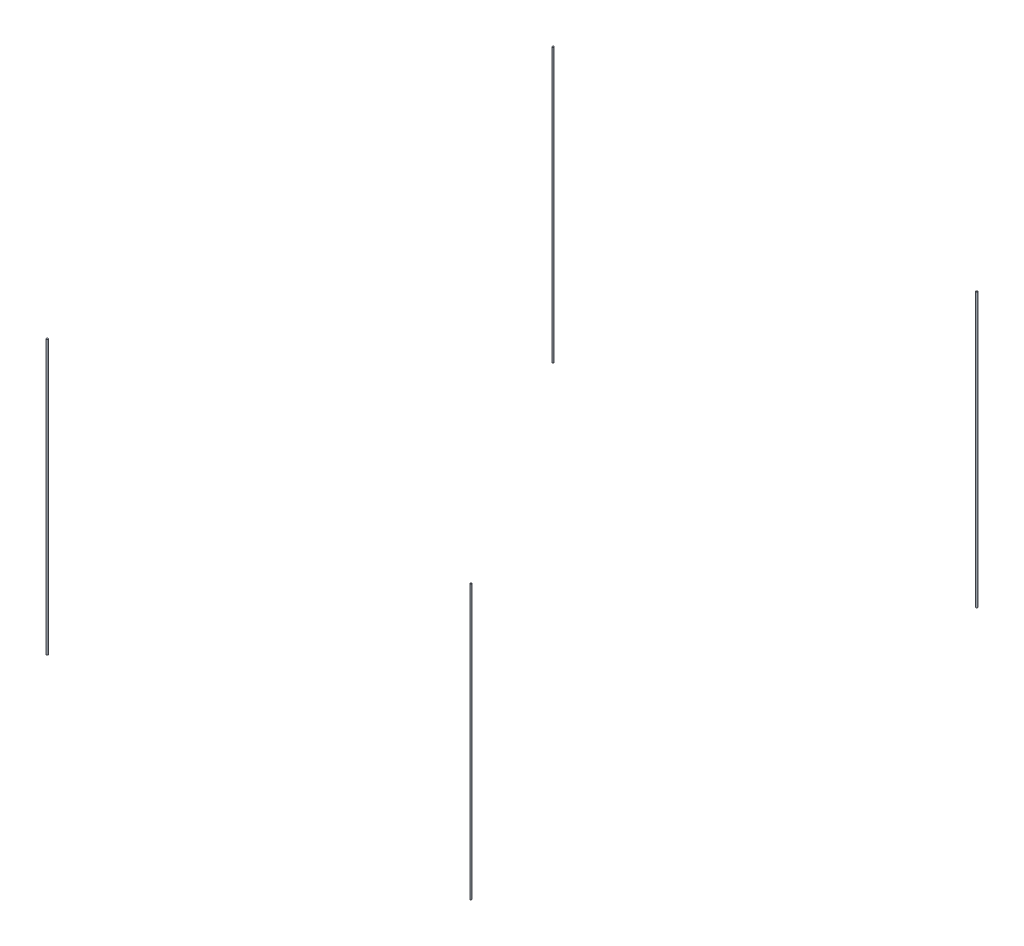
SolidWorks part; units mm, degrees
ref_plane "Front Plane" through (0, 0, 0) normal (0, 0, 1) x (1, 0, 0)
ref_plane "Top Plane" through (0, 0, 0) normal (0, 1, 0) x (1, 0, 0)
ref_plane "Right Plane" through (0, 0, 0) normal (1, 0, 0) x (0, 0, -1)
other "Configuration Table"
sketch "Sketch1" plane through (0, 0, 0) normal (0, 1, 0) x (1, 0, 0)
  line L0 (-3100, 3700) -> (-3100, 0) construction
  line L1 (-3100, 0) -> (0, 0) construction
  line L2 (0, 0) -> (0, 3700) construction
  line L3 (0, 3700) -> (-3100, 3700) construction
  circle A0 centre (-3100, 3700) radius 6
  circle A1 centre (0, 3700) radius 6
  circle A2 centre (0, 0) radius 6
  circle A3 centre (-3100, 0) radius 6
  dimension "D1" = 12
  dimension "D2" = 3700
  dimension "D3" = 3100
extrude "Boss-Extrude1" add sketch "Sketch1" along normal blind 2000
sketch "Sketch2" plane through (0, 2000, 0) normal (0, 1, 0) x (1, 0, 0)
  line L0 (-3100, 3700) -> (0, 0) construction
  point P4 (-1550, 1850)
sketch3d "3DSketch2"
  line L0 (-1550, 2000, -1850) -> (-1550, 2430, -1850)
  line L1 (-1550, 2430, -1850) -> (0, 2000, 0)
  line L2 (0, 2000, 0) -> (0, 0, 0) construction
  line L3 (-3100, 2000, -3700) -> (0, 2000, 0) construction
  line L4 (-1550, 2430, -1850) -> (-3100, 2000, -3700)
  line L5 (-1550, 2430, -1850) -> (-3100, 2000, 0)
  line L6 (-3100, 2000, 0) -> (-3100, 0, 0) construction
  line L7 (-1550, 2430, -1850) -> (0, 2000, -3700)
  line L8 (0, 2000, -3700) -> (0, 0, -3700) construction
  line L9 (0, 2000, 0) -> (-3100, 2000, 0) construction
  line L10 (-3100, 2000, 0) -> (-3100, 2000, -3700) construction
  line L11 (-1550, 2430, -1850) -> (-1550, 2000, 0) construction
  line L12 (-1550, 2430, -1850) -> (-3100, 2000, -1850) construction
  line L13 (-3100, 2000, 0) -> (-3100, 0, 0) construction
  dimension "D1" = 430
  dimension "D7" = 2451.5097
  dimension "D2" = 3700
  dimension "D3" = 3100
  dimension "D4" = 1608.5397
  dimension "D5" = 1899.3157
  dimension "D6" = 100.102
